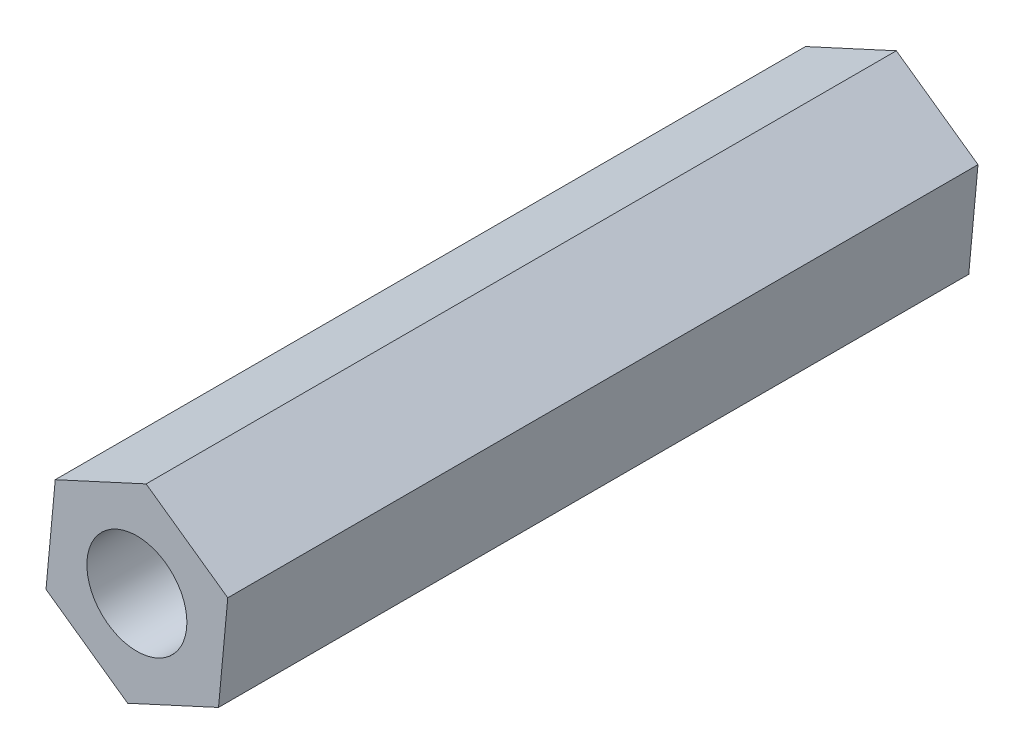
SolidWorks part; units mm, degrees
material "6061 Alloy"
ref_plane "前视基准面" through (0, 0, 0) normal (0, 0, 1) x (1, 0, 0)
ref_plane "上视基准面" through (0, 0, 0) normal (0, 1, 0) x (1, 0, 0)
ref_plane "右视基准面" through (0, 0, 0) normal (1, 0, 0) x (0, 0, -1)
sketch "Sketch1" plane through (0, 0, 0) normal (0, 0, 1) x (1, 0, 0)
  line L1 (-0.3232, -120.6294) -> (-0.693, -124.6123)
  line L2 (-0.693, -124.6123) -> (2.5713, -126.924)
  line L3 (2.5713, -126.924) -> (6.2055, -125.2528)
  line L4 (6.2055, -125.2528) -> (6.5753, -121.2699)
  line L5 (6.5753, -121.2699) -> (3.3109, -118.9583)
  line L6 (3.3109, -118.9583) -> (-0.3232, -120.6294)
  circle A0 centre (2.9411, -122.9411) radius 3.4641 construction
  circle A1 centre (2.9411, -122.9411) radius 2
  dimension "D2" = 4
  dimension "D1" = 4
extrude "Boss-Extrude1" add sketch "Sketch1" along normal blind 30
